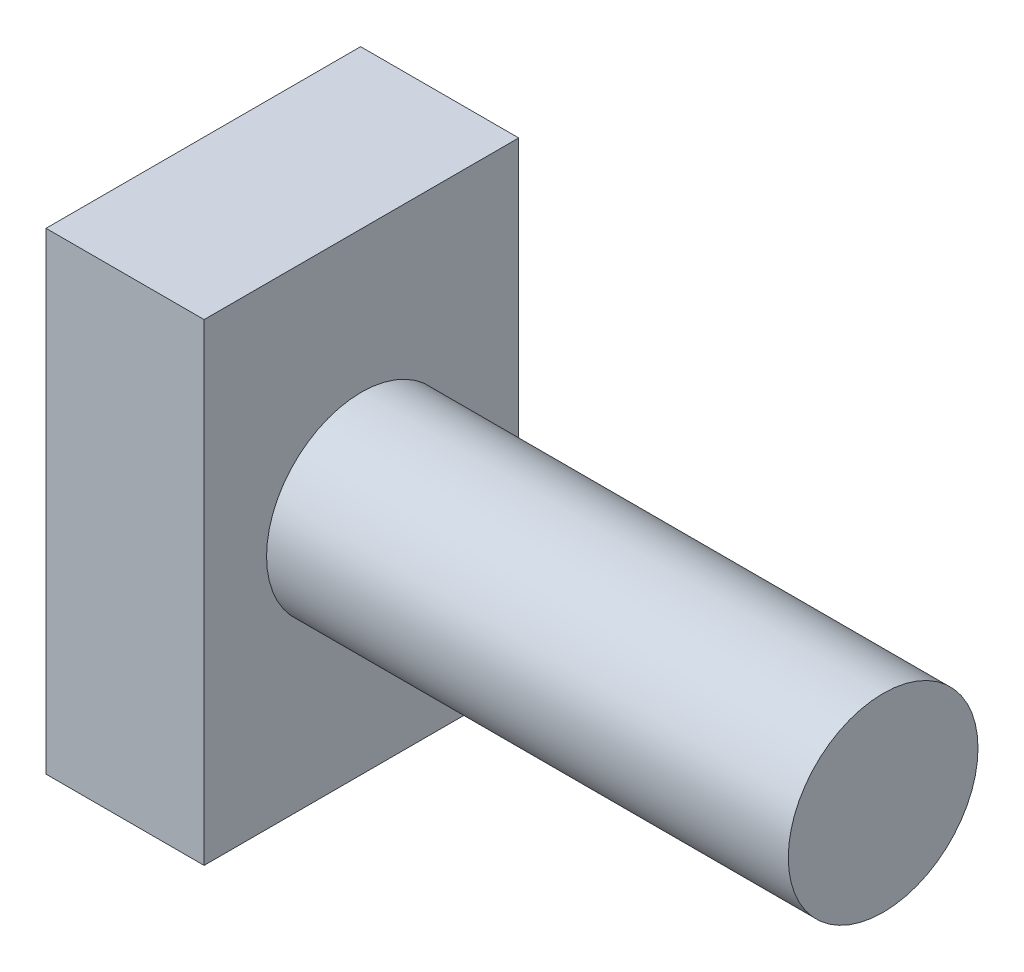
SolidWorks part; units mm, degrees
ref_plane "Спереди" through (0, 0, 0) normal (0, 0, 1) x (1, 0, 0)
ref_plane "Сверху" through (0, 0, 0) normal (0, 1, 0) x (1, 0, 0)
ref_plane "Справа" through (0, 0, 0) normal (1, 0, 0) x (0, 0, -1)
sketch "Эскиз1" plane through (0, 0, 0) normal (0, 1, 0) x (1, 0, 0)
  line L1 (-5, 9.95) -> (5, 9.95)
  line L2 (-5, 9.95) -> (-5, -9.95)
  line L3 (-5, -9.95) -> (5, -9.95)
  line L4 (5, 9.95) -> (5, -9.95)
  line L5 (-5, 9.95) -> (5, -9.95) construction
  line L6 (-5, -9.95) -> (5, 9.95) construction
  point P0 (0, 0)
  dimension "D1" = 19.9
  dimension "D2" = 10
extrude "Бобышка-Вытянуть1" add sketch "Эскиз1" along normal blind 29.9
sketch "Эскиз3" plane through (5, 0, 0) normal (1, 0, 0) x (0, 0, -1)
  line L0 (0, 29.9) -> (0, 0)
  line L1 (-9.95, 29.9) -> (9.95, 29.9) construction
  line L2 (-9.95, 0) -> (9.95, 0) construction
  circle A0 centre (0, 14.95) radius 2
  dimension "D1" = 4
sketch "Эскиз4" plane through (5, 0, 0) normal (1, 0, 0) x (0, 0, -1)
  circle A0 centre (0, 14.95) radius 6
  dimension "D1" = 12
extrude "Бобышка-Вытянуть2" add sketch "Эскиз4" along normal blind 33
sketch "Эскиз7" plane through (-5, 0, 0) normal (-1, 0, 0) x (0, 0, 1)
  circle A0 centre (0, 14.95) radius 2
extrude "Вырез-Вытянуть1" cut sketch "Эскиз7" against normal blind 9.6 contours A0
